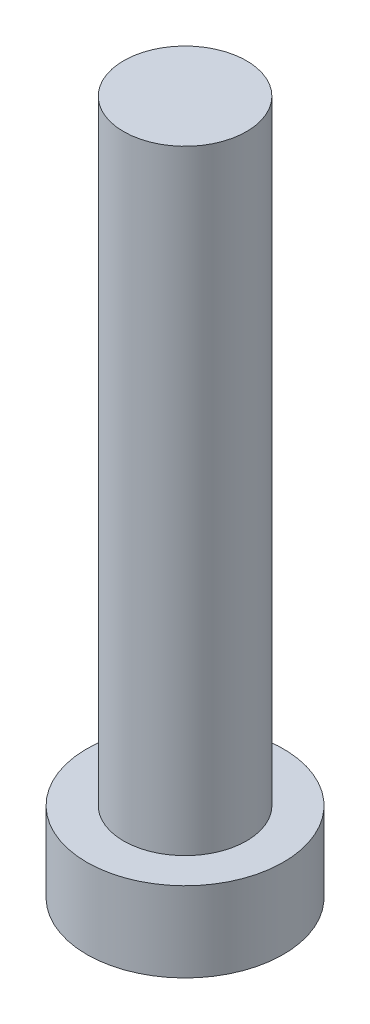
SolidWorks part; units mm, degrees
ref_plane "前视基准面" through (0, 0, 0) normal (0, 0, 1) x (1, 0, 0)
ref_plane "上视基准面" through (0, 0, 0) normal (0, 1, 0) x (1, 0, 0)
ref_plane "右视基准面" through (0, 0, 0) normal (1, 0, 0) x (0, 0, -1)
other "Configuration Table"
sketch "草图1" plane through (0, 0, 0) normal (0, 1, 0) x (1, 0, 0)
  circle A0 centre (0, 0) radius 1.6
  dimension "D1" = 3.2
extrude "凸台-拉伸1" add sketch "草图1" along normal blind 1.3
sketch "草图2" plane through (0, 0, 0) normal (0, 1, 0) x (1, 0, 0)
  circle A0 centre (0, 0) radius 1
extrude "凸台-拉伸2" add sketch "草图2" along normal blind 10 from surface at 1.3 starting at face at (0, 1.3, 1.6)
